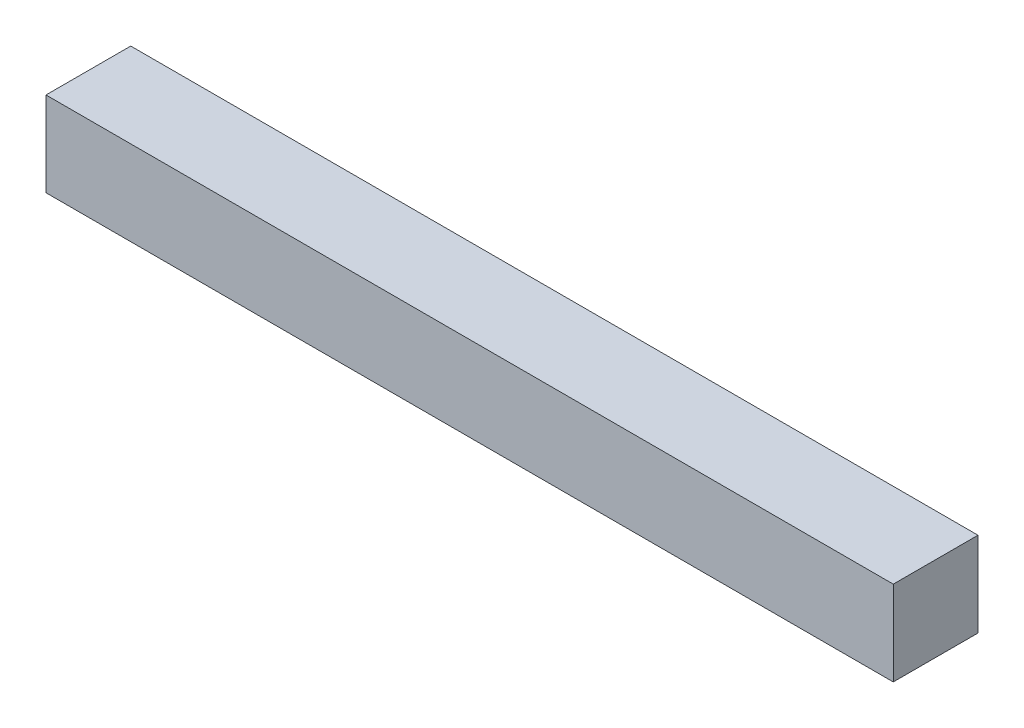
SolidWorks part; units mm, degrees
ref_plane "Front Plane" through (0, 0, 0) normal (0, 0, 1) x (1, 0, 0)
ref_plane "Top Plane" through (0, 0, 0) normal (0, 1, 0) x (1, 0, 0)
ref_plane "Right Plane" through (0, 0, 0) normal (1, 0, 0) x (0, 0, -1)
other "Configuration Table"
sketch "Sketch1" plane through (0, 0, 0) normal (0, 0, 1) x (1, 0, 0)
  line L1 (200, 1400) -> (1200, 1400)
  line L2 (200, 1400) -> (200, 1500)
  line L3 (200, 1500) -> (1200, 1500)
  line L4 (1200, 1400) -> (1200, 1500)
extrude "STORE_evaporator_1_1" add sketch "Sketch1" against normal blind 100 from offset 650 separate body
